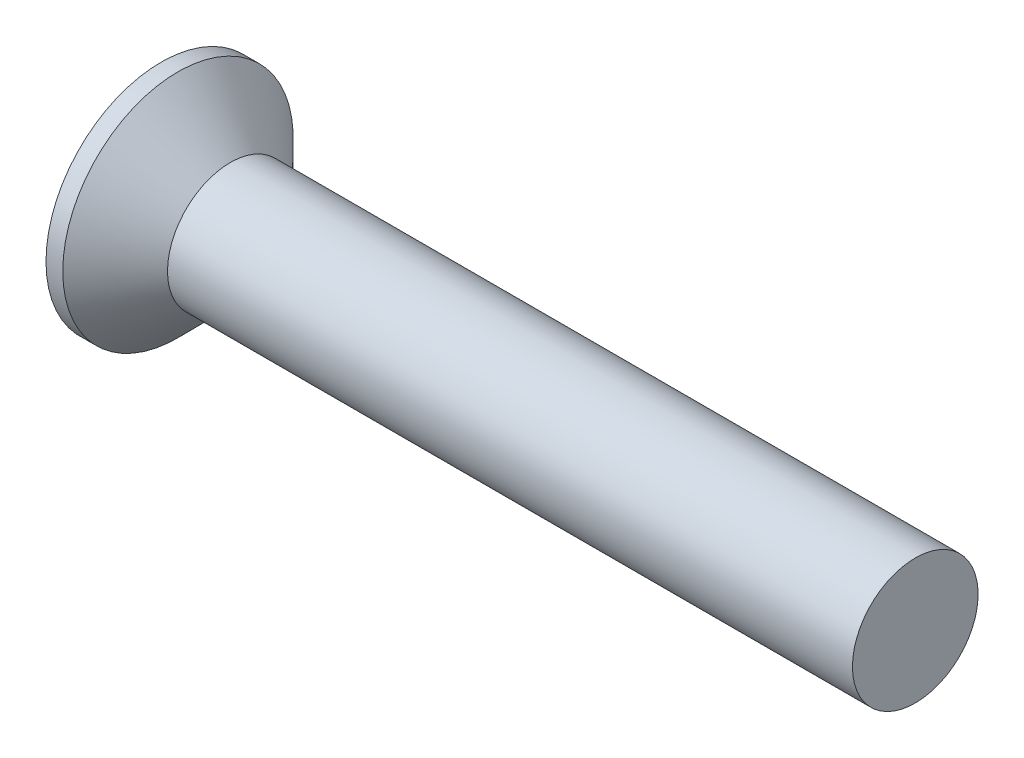
SolidWorks part; units mm, degrees
ref_plane "Plan de face" through (0, 0, 0) normal (0, 0, 1) x (1, 0, 0)
ref_plane "Plan de dessus" through (0, 0, 0) normal (0, 1, 0) x (1, 0, 0)
ref_plane "Plan de droite" through (0, 0, 0) normal (1, 0, 0) x (0, 0, -1)
sketch "Esquisse1" plane through (0, 0, 0) normal (0, 0, 1) x (1, 0, 0)
  line L0 (0, 0) -> (18, 0)
  line L1 (18, 0) -> (18, 1.5)
  line L2 (18, 1.5) -> (1.65, 1.5)
  line L4 (0, 2.75) -> (0, 0)
  line L5 (0, 2.75) -> (0.4, 2.75)
  line L6 (0.4, 2.75) -> (1.65, 1.5)
  dimension "D1" = 18
  dimension "D2" = 1.5
  dimension "D3" = 2.75
  dimension "D4" = 1.65
  dimension "D5" = 45
revolve "Révolution1" add sketch "Esquisse1" angle 360 about L0
equation "\"D3@Esquisse1\"=5.5/2"
